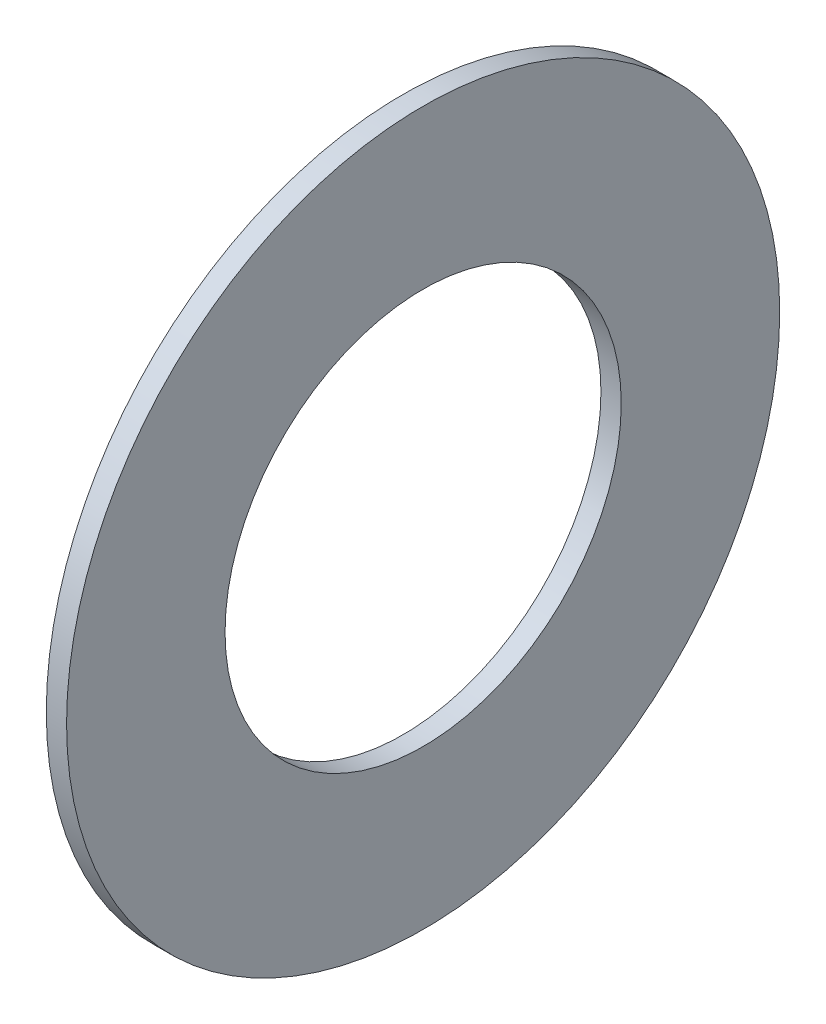
SolidWorks part; units mm, degrees
ref_plane "Front Plane" through (0, 0, 0) normal (0, 0, 1) x (1, 0, 0)
ref_plane "Top Plane" through (0, 0, 0) normal (0, 1, 0) x (1, 0, 0)
ref_plane "Right Plane" through (0, 0, 0) normal (1, 0, 0) x (0, 0, -1)
sketch "Sketch1" plane through (0, 0, 0) normal (1, 0, 0) x (0, 0, -1)
  circle A0 centre (0, 0) radius 14.2875
  circle A1 centre (0, 0) radius 7.9375
  dimension "OD" = 28.575
  dimension "Shaft Dia" = 15.875
extrude "Extrude1" add sketch "Sketch1" along normal blind 0.8128
